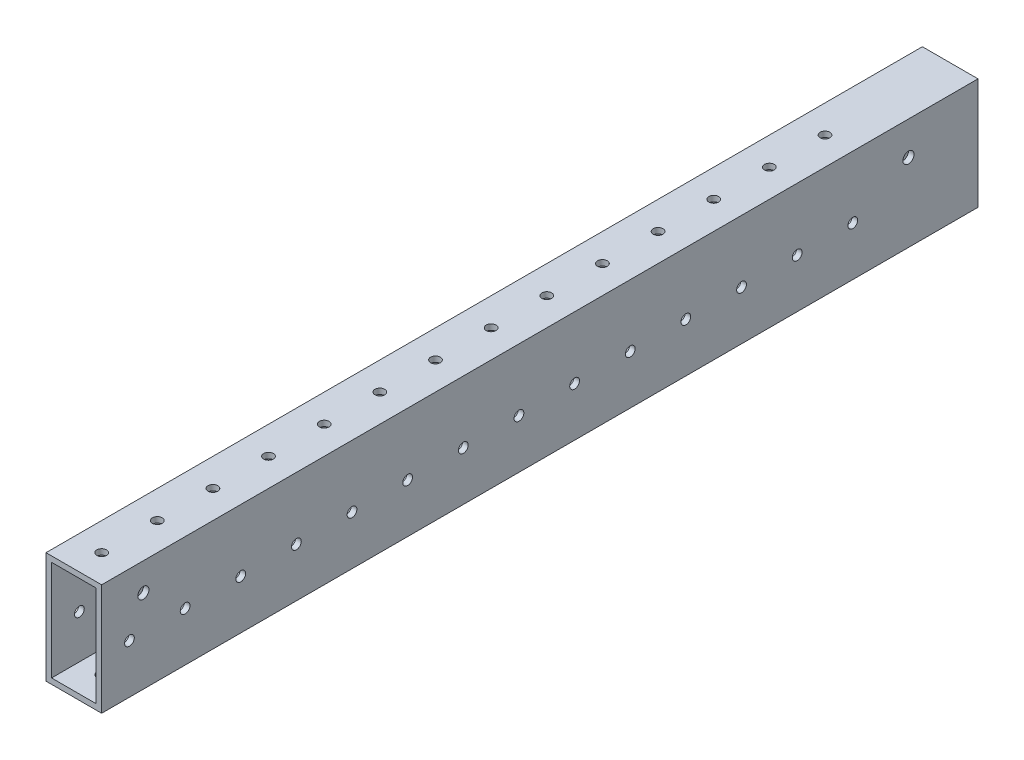
SolidWorks part; units mm, degrees
material "1060-H12"
ref_plane "前视基准面" through (0, 0, 0) normal (0, 0, 1) x (1, 0, 0)
ref_plane "上视基准面" through (0, 0, 0) normal (0, 1, 0) x (1, 0, 0)
ref_plane "右视基准面" through (0, 0, 0) normal (1, 0, 0) x (0, 0, -1)
other "Configuration Table"
sketch "草图1" plane through (0, 0, 0) normal (0, 0, 1) x (1, 0, 0)
  line L1 (0, 0) -> (20, 0)
  line L2 (0, 0) -> (0, 40)
  line L3 (0, 40) -> (20, 40)
  line L4 (20, 0) -> (20, 40)
  line L5 (2, 2) -> (18, 2)
  line L6 (2, 2) -> (2, 38)
  line L7 (2, 38) -> (18, 38)
  line L8 (18, 2) -> (18, 38)
  dimension "D1" = 20
  dimension "D2" = 40
  dimension "D3" = 2
  dimension "D4" = 2
  dimension "D5" = 2
  dimension "D6" = 2
extrude "凸台-拉伸1" add sketch "草图1" along normal blind 315
sketch "草图2" plane through (20, 0, 0) normal (1, 0, 0) x (0, 0, -1)
  line L0 (-328.752, 30) -> (-7.0045, 30) construction
  line L1 (0, 0) -> (0, 40) construction
  line L2 (-315, 40) -> (0, 40) construction
  line L4 (-315, 0) -> (-315, 40) construction
  line L6 (-315, 0) -> (0, 0) construction
  circle A0 centre (-300, 30) radius 2
  circle A2 centre (-25, 28) radius 2
  dimension "D1" = 4
  dimension "D2" = 4
  dimension "D3" = 25
  dimension "D4" = 15
  dimension "D5" = 30
  dimension "D6" = 12
extrude "切除-拉伸1" cut sketch "草图2" against normal through all
sketch "草图3" plane through (0, 0, 0) normal (0, -1, 0) x (-1, 0, 0)
  circle A0 centre (-10, -305) radius 1.75
  circle A1 centre (-10, -285) radius 1.75
  circle A2 centre (-10, -265) radius 1.75
  circle A3 centre (-10, -245) radius 1.75
  circle A4 centre (-10, -225) radius 1.75
  circle A5 centre (-10, -205) radius 1.75
  circle A6 centre (-10, -185) radius 1.75
  circle A7 centre (-10, -165) radius 1.75
  circle A8 centre (-10, -145) radius 1.75
  circle A9 centre (-10, -125) radius 1.75
  circle A10 centre (-10, -105) radius 1.75
  circle A11 centre (-10, -85) radius 1.75
  circle A12 centre (-10, -65) radius 1.75
  circle A13 centre (-10, -45) radius 1.75
  circle A14 centre (-10, -305) radius 3 construction
  dimension "D2" = 20
  dimension "D3" = 1.25
  dimension "D1" = 14
extrude "切除-拉伸2" cut sketch "草图3" against normal through all
sketch "草图4" plane through (0, 0, 0) normal (-1, 0, 0) x (0, 0, 1)
  circle A0 centre (305, 17.65) radius 1.75
  circle A1 centre (285, 17.65) radius 1.75
  circle A2 centre (265, 17.65) radius 1.75
  circle A3 centre (245, 17.65) radius 1.75
  circle A4 centre (225, 17.65) radius 1.75
  circle A5 centre (205, 17.65) radius 1.75
  circle A6 centre (185, 17.65) radius 1.75
  circle A7 centre (165, 17.65) radius 1.75
  circle A8 centre (145, 17.65) radius 1.75
  circle A9 centre (125, 17.65) radius 1.75
  circle A10 centre (105, 17.65) radius 1.75
  circle A11 centre (85, 17.65) radius 1.75
  circle A12 centre (65, 17.65) radius 1.75
  circle A13 centre (45, 17.65) radius 1.75
  dimension "D2" = 20
  dimension "D3" = 3.5
  dimension "D1" = 14
sketch "草图5" plane through (20, 0, 0) normal (1, 0, 0) x (0, 0, -1)
  circle A0 centre (-305, 17.65) radius 1.75
  circle A1 centre (-285, 17.65) radius 1.75
  circle A2 centre (-265, 17.65) radius 1.75
  circle A3 centre (-245, 17.65) radius 1.75
  circle A4 centre (-225, 17.65) radius 1.75
  circle A5 centre (-205, 17.65) radius 1.75
  circle A6 centre (-185, 17.65) radius 1.75
  circle A7 centre (-165, 17.65) radius 1.75
  circle A8 centre (-145, 17.65) radius 1.75
  circle A9 centre (-125, 17.65) radius 1.75
  circle A10 centre (-105, 17.65) radius 1.75
  circle A11 centre (-85, 17.65) radius 1.75
  circle A12 centre (-65, 17.65) radius 1.75
  circle A13 centre (-45, 17.65) radius 1.75
  dimension "D2" = 20
  dimension "D3" = 3.5
  dimension "D1" = 14
extrude "切除-拉伸4" cut sketch "草图5" against normal through all
